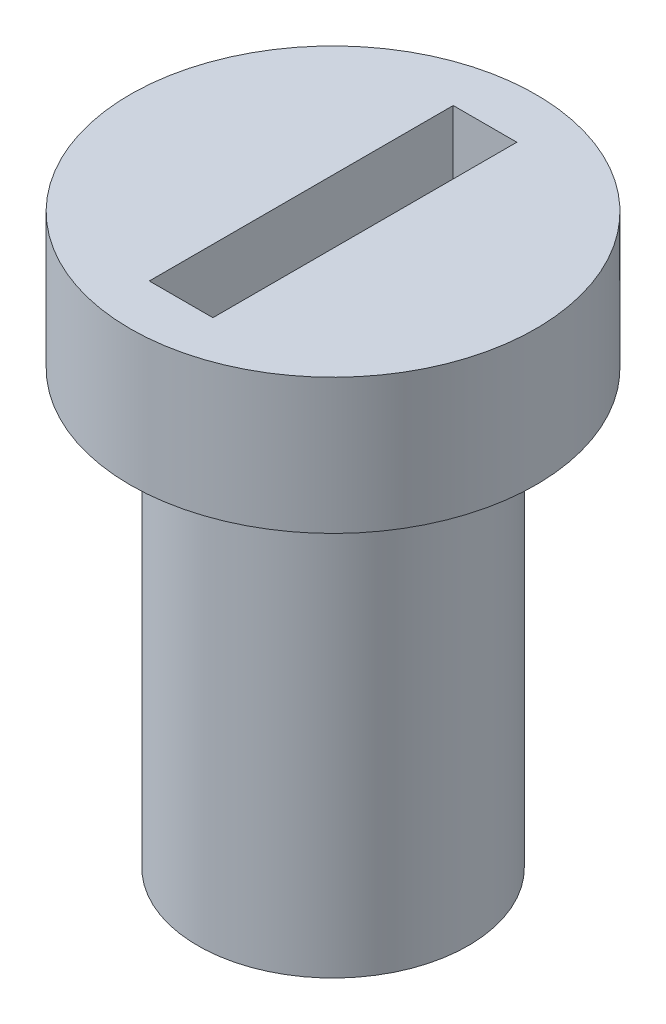
SolidWorks part; units mm, degrees
ref_plane "前视基准面" through (0, 0, 0) normal (0, 0, 1) x (1, 0, 0)
ref_plane "上视基准面" through (0, 0, 0) normal (0, 1, 0) x (1, 0, 0)
ref_plane "右视基准面" through (0, 0, 0) normal (1, 0, 0) x (0, 0, -1)
other "Configuration Table"
sketch "草图1" plane through (0, 0, 0) normal (0, 1, 0) x (1, 0, 0)
  circle A0 centre (0, 0) radius 7.5
  dimension "D1" = 15
extrude "凸台-拉伸1" add sketch "草图1" along normal blind 5
ref_plane "基准面1" through (0, 0, 0) normal (0, -1, 0) x (-1, 0, 0)
sketch "草图2" plane through (0, 0, 0) normal (0, -1, 0) x (-1, 0, 0)
  circle A0 centre (0, 0) radius 5
  dimension "D1" = 10
extrude "凸台-拉伸2" add sketch "草图2" along normal blind 16
cosmetic thread "装饰螺纹线1" parameters "D2"=9
ref_plane "基准面2" through (0, 5, 0) normal (0, 1, 0) x (1, 0, 0)
sketch "草图3" plane through (0, 5, 0) normal (0, 1, 0) x (1, 0, 0)
  line L0 (0, 0) -> (7.3803, 0) construction
  line L1 (0, 0) -> (0, 6.0932) construction
  line L3 (-1.1755, 5.6171) -> (1.1755, 5.6171)
  line L4 (-1.1755, 5.6171) -> (-1.1755, -5.6171)
  line L5 (-1.1755, -5.6171) -> (1.1755, -5.6171)
  line L6 (1.1755, 5.6171) -> (1.1755, -5.6171)
extrude "切除-拉伸1" cut sketch "草图3" against normal blind 3
